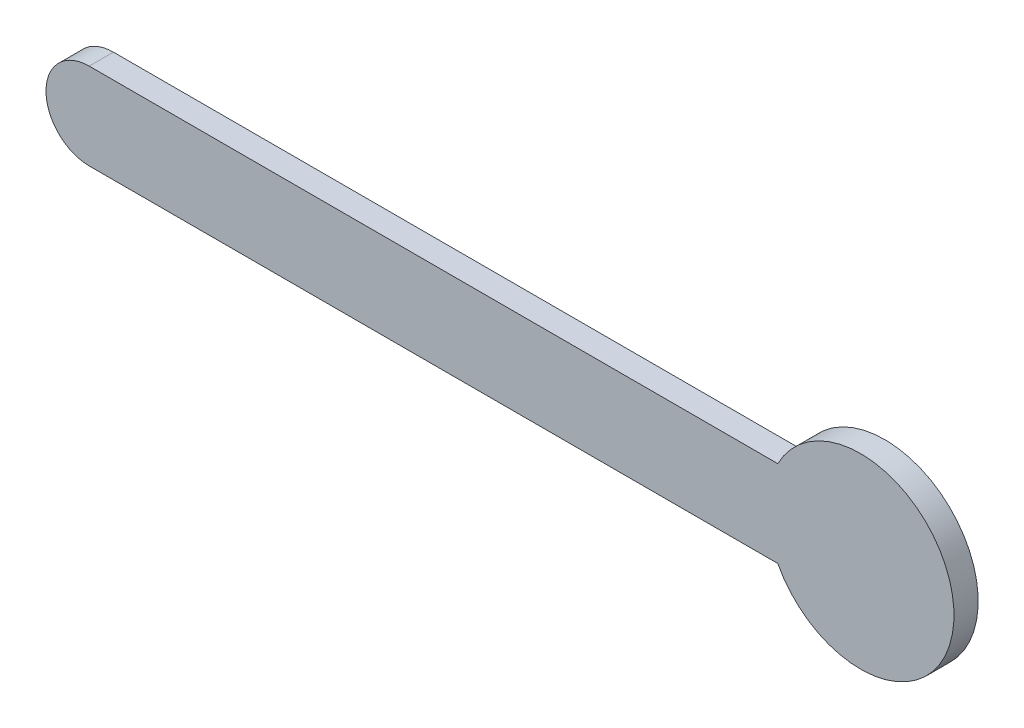
SolidWorks part; units mm, degrees
ref_plane "前视基准面" through (0, 0, 0) normal (0, 0, 1) x (1, 0, 0)
ref_plane "上视基准面" through (0, 0, 0) normal (0, 1, 0) x (1, 0, 0)
ref_plane "右视基准面" through (0, 0, 0) normal (1, 0, 0) x (0, 0, -1)
other "Configuration Table"
sketch "草图1" plane through (0, 0, 0) normal (0, 0, 1) x (1, 0, 0)
  line L0 (0, 0) -> (223, 0) construction
  line L1 (0, 12.5) -> (199.0678, 12.5)
  line L2 (0, -12.5) -> (199.0678, -12.5)
  arc A0 (0, 12.5) -> (0, -12.5) centre (0, 0) ccw
  arc A1 (199.0678, -12.5) -> (199.0678, 12.5) centre (223, 0) ccw
  dimension "D1" = 12.5
  dimension "D2" = 27
  dimension "D3" = 223
extrude "凸台-拉伸1" add sketch "草图1" along normal blind 7
sketch "草图2" plane through (0, 0, 7) normal (0, 0, 1) x (1, 0, 0)
  circle A0 centre (0, 0) radius 12.5
  circle A1 centre (223, 0) radius 27
